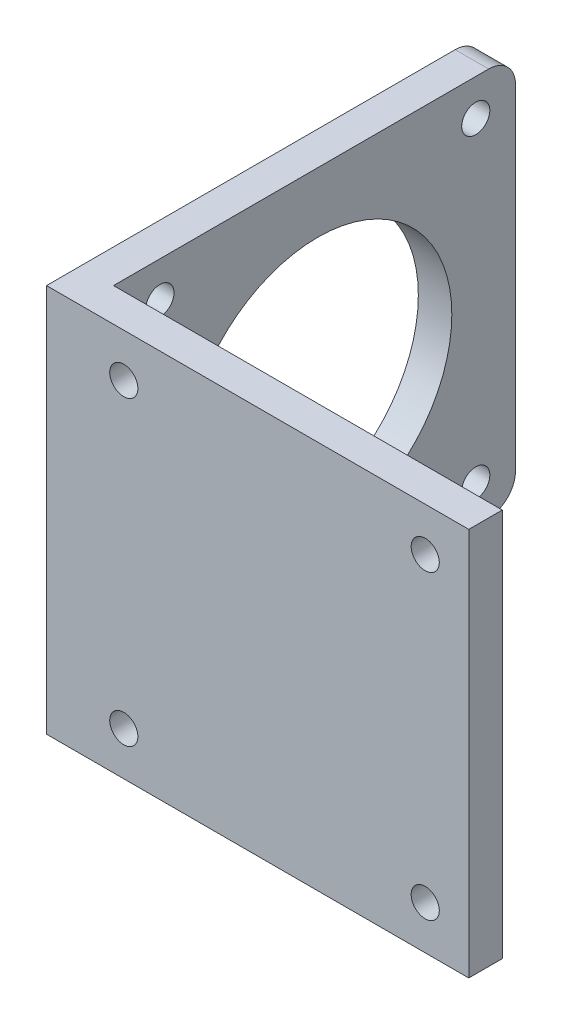
SolidWorks part; units mm, degrees
ref_plane "Front Plane" through (0, 0, 0) normal (0, 0, 1) x (1, 0, 0)
ref_plane "Top Plane" through (0, 0, 0) normal (0, 1, 0) x (1, 0, 0)
ref_plane "Right Plane" through (0, 0, 0) normal (1, 0, 0) x (0, 0, -1)
sketch "Sketch2" plane through (0, 0, 0) normal (0, 1, 0) x (1, 0, 0)
  line L0 (0, 0) -> (0, 65)
  line L1 (0, 65) -> (5, 65)
  line L2 (5, 65) -> (5, 5)
  line L3 (5, 5) -> (63.031, 5)
  line L4 (63.031, 5) -> (63.031, 0)
  line L5 (63.031, 0) -> (0, 0)
  dimension "D1" = 5
  dimension "D2" = 65
extrude "Boss-Extrude2" add sketch "Sketch2" along normal blind 58
sketch "Sketch3" plane through (5, 0, 0) normal (-1, 0, 0) x (0, 0, 1)
  line L0 (-65, 29) -> (-5, 29) construction
  line L1 (-65, 58) -> (-65, 0) construction
  line L24 (-5, 0) -> (-5, 58) construction
  line L25 (-65, 0) -> (0, 0) construction
  line L26 (-65, 58) -> (0, 58) construction
  line L27 (-5, 58) -> (-5, 0) construction
  circle A0 centre (-35.5, 29) radius 20
  point P49 (-35.5, 29)
  dimension "D3" = 40
  dimension "D1" = 29.5
extrude "Cut-Extrude3" cut sketch "Sketch3" along normal through all
sketch "Sketch5" plane through (0, 0, 0) normal (0, 0, -1) x (-1, 0, 0)
  line L0 (-56.531, 29) -> (-63.031, 29) construction
  line L1 (-63.031, 58) -> (-63.031, 0) construction
  line L2 (-34.031, 6.5) -> (-34.031, 0) construction
  line L3 (0, 0) -> (-63.031, 0) construction
  line L7 (-56.531, 6.5) -> (-11.531, 6.5) construction
  line L8 (-56.531, 6.5) -> (-56.531, 51.5) construction
  line L9 (-56.531, 51.5) -> (-11.531, 51.5) construction
  line L10 (-11.531, 6.5) -> (-11.531, 51.5) construction
  line L11 (-56.531, 6.5) -> (-11.531, 51.5) construction
  line L12 (-56.531, 51.5) -> (-11.531, 6.5) construction
  point P12 (-34.031, 29)
  point P18 (-11.531, 6.5)
  point P19 (-11.531, 51.5)
  point P20 (-56.531, 51.5)
  point P21 (-56.531, 6.5)
  dimension "D1" = 45
  dimension "D2" = 45
hole_wizard "M5x0.8 Tapped Hole3" positions "Sketch20" profile "Sketch19" tap size "M5x0.8" standard "ANSI Metric" end condition through all
sketch "Sketch20" plane through (0, 0, 0) normal (0, 0, 1) x (1, 0, 0)
  point P0 (11.531, 6.5)
  point P3 (11.531, 51.5)
  point P6 (56.531, 51.5)
  point P9 (56.531, 6.5)
sketch "Sketch19" plane through (11.531, 6.5, 0) normal (1, 0, 0) x (0, -1, 0)
  line L0 (0, 0) -> (0, 65)
  line L1 (0, 65) -> (2.1, 65)
  line L2 (2.1, 65) -> (2.1, 0)
  line L5 (2.1, 0) -> (0, 0)
  line L11 (0, -6.35) -> (0, 107.95) construction
  dimension "Thru Tap Drill Dia." = 4.2
  dimension "Thru Tap Drill Depth" = 65
cosmetic thread "Hole Thread9" parameters "D2"=5
cosmetic thread "Hole Thread10" parameters "D2"=5
cosmetic thread "Hole Thread11" parameters "D2"=5
cosmetic thread "Hole Thread12" parameters "D2"=5
sketch "Sketch6" plane through (0, 0, 0) normal (1, 0, 0) x (0, 0, -1)
  line L1 (11.9268, 5.4268) -> (59.0732, 5.4268) construction
  line L2 (11.9268, 5.4268) -> (11.9268, 52.5732) construction
  line L3 (11.9268, 52.5732) -> (59.0732, 52.5732) construction
  line L4 (59.0732, 5.4268) -> (59.0732, 52.5732) construction
  line L5 (11.9268, 5.4268) -> (59.0732, 52.5732) construction
  line L6 (11.9268, 52.5732) -> (59.0732, 5.4268) construction
  circle A0 centre (35.5, 29) radius 33.3375 construction
  point P0 (35.5, 29)
  point P7 (11.9268, 52.5732)
  point P8 (59.0732, 52.5732)
  point P9 (59.0732, 5.4268)
  point P10 (11.9268, 5.4268)
  dimension "D1" = 66.675
hole_wizard "M5x0.8 Tapped Hole2" positions "Sketch14" profile "Sketch13" tap size "M5x0.8" standard "ANSI Metric" end condition through all
sketch "Sketch14" plane through (0, 0, 0) normal (-1, 0, 0) x (0, 0, 1)
  point P0 (-11.9268, 5.4268)
  point P3 (-11.9268, 52.5732)
  point P6 (-59.0732, 52.5732)
  point P9 (-59.0732, 5.4268)
sketch "Sketch13" plane through (0, 5.4268, -11.9268) normal (0, 1, 0) x (0, 0, 1)
  line L0 (0, 0) -> (0, 63.031)
  line L1 (0, 63.031) -> (2.1, 63.031)
  line L2 (2.1, 63.031) -> (2.1, 0)
  line L5 (2.1, 0) -> (0, 0)
  line L11 (0, -6.35) -> (0, 107.95) construction
  dimension "Thru Tap Drill Dia." = 4.2
  dimension "Thru Tap Drill Depth" = 63.031
cosmetic thread "Hole Thread5" parameters "D2"=5
cosmetic thread "Hole Thread6" parameters "D2"=5
cosmetic thread "Hole Thread7" parameters "D2"=5
cosmetic thread "Hole Thread8" parameters "D2"=5
fillet "Fillet1" radius 4 2 edges at (2.5, 58, -65) (2.5, 0, -65)
